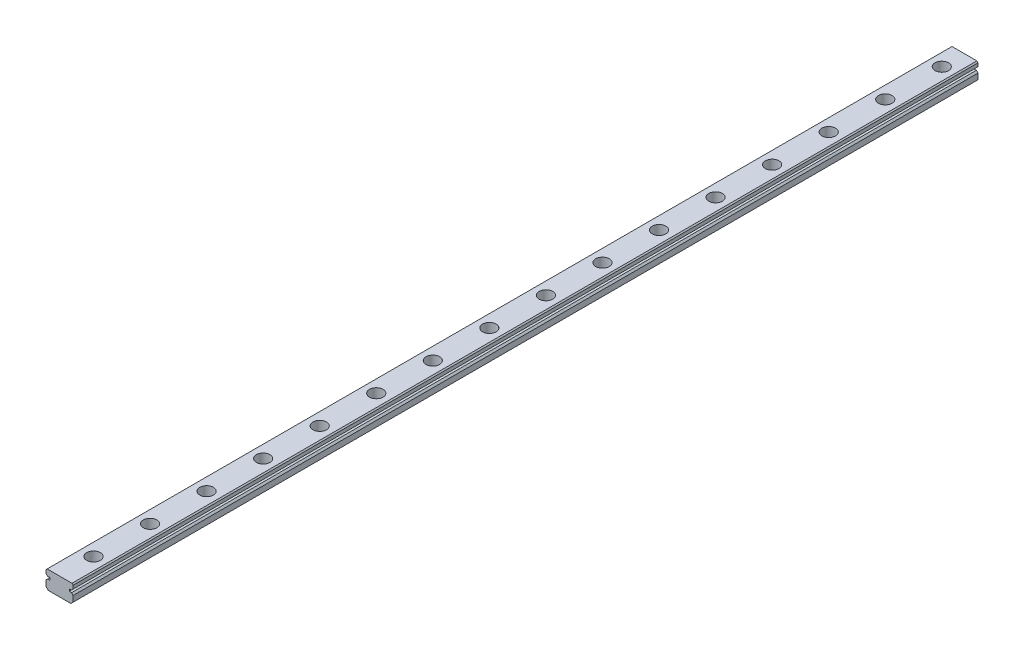
SolidWorks part; units mm, degrees
material "AISI 1020 Steel, Cold Rolled"
ref_plane "Front Plane" through (0, 0, 0) normal (0, 0, 1) x (1, 0, 0)
ref_plane "Top Plane" through (0, 0, 0) normal (0, 1, 0) x (1, 0, 0)
ref_plane "Right Plane" through (0, 0, 0) normal (1, 0, 0) x (0, 0, -1)
ref_plane "RailEndPlane" through (0, 0, 400) normal (0, 0, 1) x (1, 0, 0)
sketch "MainProfile" plane through (0, 0, 0) normal (0, 0, 1) x (1, 0, 0)
  line L0 (0, 0) -> (0, 3.5858)
  line L1 (0, 8) -> (12, 8)
  line L2 (12, 8) -> (12, 6)
  line L3 (12, 0) -> (0, 0)
  line L4 (6, 8) -> (6, -2.3077) construction
  line L5 (0, 6) -> (0.7071, 5.2929)
  line L6 (0.7071, 5.2929) -> (1.7071, 5.2929)
  line L7 (1.7071, 5.2929) -> (1.7071, 4.2929)
  line L8 (1.7071, 4.2929) -> (0.7071, 4.2929)
  line L9 (0.7071, 4.2929) -> (0, 3.5858)
  line L10 (0, 6) -> (0, 8)
  line L11 (11.2929, 4.2929) -> (12, 3.5858)
  line L12 (10.2929, 4.2929) -> (11.2929, 4.2929)
  line L13 (10.2929, 5.2929) -> (10.2929, 4.2929)
  line L14 (11.2929, 5.2929) -> (10.2929, 5.2929)
  line L15 (12, 6) -> (11.2929, 5.2929)
  line L16 (12, 3.5858) -> (12, 0)
  dimension "D1" = 8
  dimension "D2" = 12
  dimension "D3" = 270
  dimension "D4" = 1
  dimension "D5" = 2
  dimension "D6" = 2.7071
extrude "Main Extrusion" add sketch "MainProfile" along normal up to surface (400 mm away) up to plane "RailEndPlane"
sketch "First Hole Position" plane through (0, 0, 0) normal (0, 1, 0) x (1, 0, 0)
  point P0 (6, -10)
  dimension "D1" = 10
  dimension "D2" = 6
hole_wizard "Mounting Hole Master" positions "Sketch2" profile "Sketch3" legacy
sketch "Sketch2" plane through (0, 8, 0) normal (0, 1, 0) x (1, 0, 0)
  point P0 (6, -10)
sketch "Sketch3" plane through (6, 8, 10) normal (1, 0, 0) x (0, 0, 1)
  line L0 (0, 0) -> (0, 9.9216)
  line L1 (0, 9.9216) -> (1.75, 9.9216)
  line L2 (1.75, 9.9216) -> (1.75, 4.5)
  line L3 (1.75, 4.5) -> (3, 4.5)
  line L4 (3, 4.5) -> (3, 0)
  line L5 (3, 0) -> (0, 0)
  line L6 (0, 110) -> (0, -10) construction
  dimension "Diameter" = 3.5
  dimension "Depth" = 10
  dimension "C-Bore Diameter" = 6
  dimension "C-Bore Depth" = 4.5
pattern_linear "Mounting Holes Pattern" count 16 spacing 25 along (0, 0, 1) of "Mounting Hole Master"
chamfer "Rail Top Chamfer" distance 0.5 angle 45 2 edges at (0, 8, 200) (12, 8, 200)
chamfer "Rail Bottom Chamfer" distance 1 angle 45 2 edges at (0, 0, 200) (12, 0, 200)
